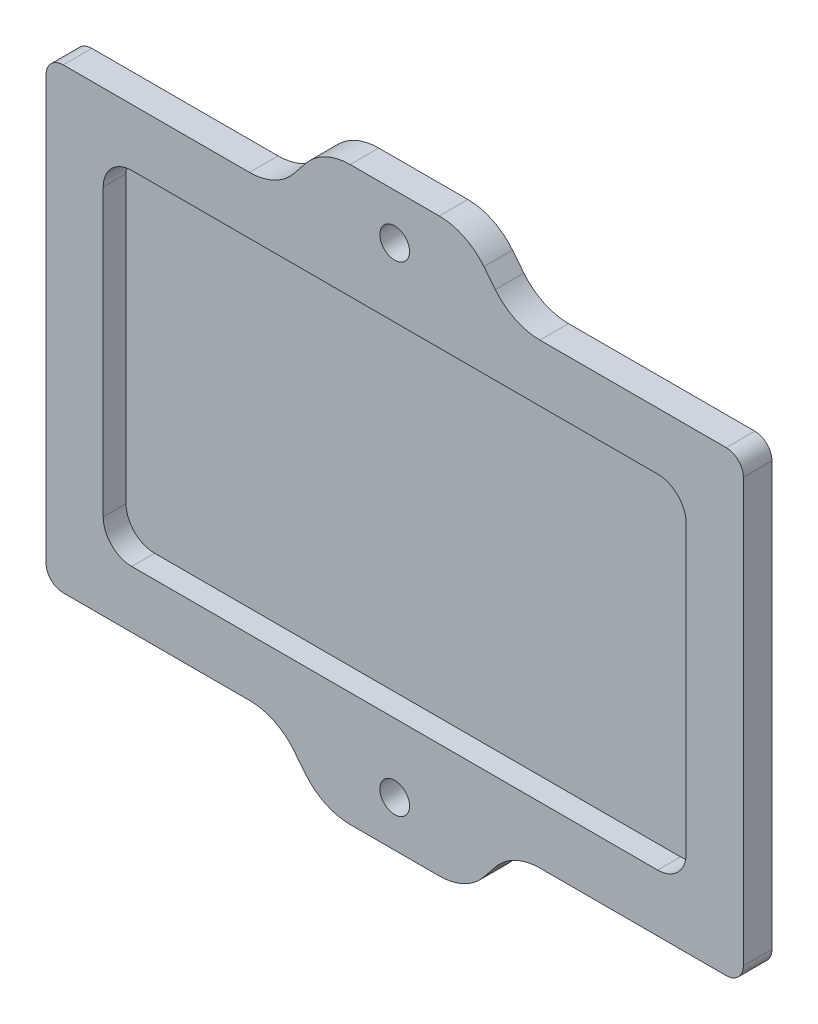
SolidWorks part; units mm, degrees
material "6063-O"
ref_plane "Front Plane" through (0, 0, 0) normal (0, 0, 1) x (1, 0, 0)
ref_plane "Top Plane" through (0, 0, 0) normal (0, 1, 0) x (1, 0, 0)
ref_plane "Right Plane" through (0, 0, 0) normal (1, 0, 0) x (0, 0, -1)
sketch "Sketch1" plane through (0, 0, 0) normal (0, 0, 1) x (1, 0, 0)
  line L1 (-42.6192, 65.8813) -> (73.3808, 65.8813)
  line L2 (-45.6192, 62.8813) -> (-45.6192, -41.1187)
  line L3 (-42.6192, -44.1187) -> (73.3808, -44.1187)
  line L4 (76.3808, 62.8813) -> (76.3808, -41.1187)
  arc A0 (-45.6192, -41.1187) -> (-42.6192, -44.1187) centre (-42.6192, -41.1187) ccw
  arc A1 (73.3808, -44.1187) -> (76.3808, -41.1187) centre (73.3808, -41.1187) ccw
  arc A2 (76.3808, 62.8813) -> (73.3808, 65.8813) centre (73.3808, 62.8813) ccw
  arc A3 (-45.6192, 62.8813) -> (-42.6192, 65.8813) centre (-42.6192, 62.8813) cw
  point P6 (-45.6192, -44.1187)
  point P11 (76.3808, 65.8813)
  point P14 (-45.6192, 65.8813)
  dimension "D3" = 3
  dimension "D1" = 122
  dimension "D2" = 110
extrude "Boss-Extrude1" add sketch "Sketch1" along normal blind 5
sketch "Sketch3" plane through (0, 0, 5) normal (0, 0, 1) x (1, 0, 0)
  line L0 (-45.6192, 62.8813) -> (-45.6192, -41.1187) construction
  line L2 (73.3808, 65.8813) -> (-42.6192, 65.8813) construction
  line L5 (-42.6192, -44.1187) -> (73.3808, -44.1187) construction
  line L6 (15.3808, 24.2476) -> (15.3808, -7.2931) construction
  line L8 (40.7873, 50.8813) -> (76.3808, 50.8813)
  line L9 (76.3808, -41.1187) -> (76.3808, 62.8813) construction
  line L10 (23.9808, 65.8813) -> (32.9787, 54.6343)
  line L11 (23.9808, 65.8813) -> (13.4808, 65.8813)
  line L13 (-10.0257, 50.8813) -> (-45.6192, 50.8813)
  line L14 (6.7808, 65.8813) -> (-2.217, 54.6343)
  line L15 (-57.8903, 10.8813) -> (91.1459, 10.8813) construction
  line L16 (40.7873, -29.1187) -> (76.3808, -29.1187)
  line L17 (23.9808, -44.1187) -> (32.9787, -32.8716)
  line L18 (6.7808, -44.1187) -> (-2.217, -32.8716)
  line L19 (-10.0257, -29.1187) -> (-45.6192, -29.1187)
  line L20 (-45.6192, 50.8813) -> (-45.6192, 81.1365)
  line L21 (-45.6192, 81.1365) -> (6.7808, 81.1365)
  line L22 (6.7808, 81.1365) -> (6.7808, 65.8813)
  line L23 (23.9808, 81.1365) -> (23.9808, 65.8813)
  line L24 (76.3808, 50.8813) -> (76.3808, 81.1365)
  line L25 (76.3808, 81.1365) -> (23.9808, 81.1365)
  line L26 (76.3808, -29.1187) -> (76.3808, -59.3739)
  line L27 (23.9808, -59.3739) -> (23.9808, -44.1187)
  line L28 (76.3808, -59.3739) -> (23.9808, -59.3739)
  line L29 (-45.6192, -29.1187) -> (-45.6192, -59.3739)
  line L30 (6.7808, -59.3739) -> (6.7808, -44.1187)
  line L31 (-45.6192, -59.3739) -> (6.7808, -59.3739)
  circle A0 centre (15.3808, 52.8813) radius 2.6
  circle A1 centre (15.3808, -31.1187) radius 2.6
  arc A2 (40.7873, 50.8813) -> (32.9787, 54.6343) centre (40.7873, 60.8813) cw
  arc A3 (-10.0257, 50.8813) -> (-2.217, 54.6343) centre (-10.0257, 60.8813) ccw
  arc A4 (40.7873, -29.1187) -> (32.9787, -32.8716) centre (40.7873, -39.1187) ccw
  arc A5 (-10.0257, -29.1187) -> (-2.217, -32.8716) centre (-10.0257, -39.1187) cw
  arc M1 (-45.6192, -41.1187) -> (-42.6192, -44.1187) centre (-42.6192, -41.1187) ccw
  line M2 (-42.6192, -44.1187) -> (73.3808, -44.1187)
  arc M3 (73.3808, -44.1187) -> (76.3808, -41.1187) centre (73.3808, -41.1187) ccw
  line M4 (76.3808, -41.1187) -> (76.3808, 62.8813)
  arc M5 (76.3808, 62.8813) -> (73.3808, 65.8813) centre (73.3808, 62.8813) ccw
  line M6 (73.3808, 65.8813) -> (-42.6192, 65.8813)
  arc M7 (-42.6192, 65.8813) -> (-45.6192, 62.8813) centre (-42.6192, 62.8813) ccw
  line M8 (-45.6192, 62.8813) -> (-45.6192, -41.1187)
  dimension "D2" = 0
  dimension "D4" = 13
  dimension "D5" = 10
  dimension "D1" = 52.4
  dimension "D6" = 55
  dimension "D7" = 40
extrude "Cut-Extrude1" cut sketch "Sketch3" against normal blind 10 contours L22 L21 L20 M7 M6 | L13 A3 L14 M6 M7 M8 | L24 L25 L23 M6 M5 | A2 L8 L10 M4 M5 M6 | L16 A4 L17 M2 M3 M4 | L28 L26 L27 M3 M2 | A5 L19 L18 M8 M1 M2 | L29 L31 L30 M2 M1 | A1
fillet "Fillet1" radius 10 4 edges at (6.7808, 65.8813, 2.5) (23.9808, 65.8813, 2.5) (6.7808, -44.1187, 2.5) (23.9808, -44.1187, 2.5)
fillet "Fillet2" radius 3 4 edges at (-45.6192, 50.8813, 2.5) (-45.6192, -29.1187, 2.5) (76.3808, 50.8813, 2.5) (76.3808, -29.1187, 2.5)
sketch "Sketch4" plane through (0, 0, 5) normal (0, 0, 1) x (1, 0, 0)
  line L0 (76.3808, -26.1187) -> (76.3808, 47.8813) construction
  circle A0 centre (15.3808, 52.8813) radius 2.6
  dimension "D1" = 61
  dimension "D2" = 13
  dimension "D3" = 5.2
extrude "Cut-Extrude2" cut sketch "Sketch4" against normal blind 10
sketch "Sketch5" plane through (0, 0, 5) normal (0, 0, 1) x (1, 0, 0)
  line L0 (-45.6192, 47.8813) -> (-45.6192, -26.1187) construction
  line L1 (-30.6192, 40.8813) -> (61.3808, 40.8813)
  line L2 (-35.6192, 35.8813) -> (-35.6192, -14.1187)
  line L3 (-30.6192, -19.1187) -> (61.3808, -19.1187)
  line L4 (66.3808, 35.8813) -> (66.3808, -14.1187)
  line L5 (-10.0257, 50.8813) -> (-42.6192, 50.8813) construction
  line L6 (-10.0257, -29.1187) -> (-42.6192, -29.1187) construction
  line L7 (76.3808, -26.1187) -> (76.3808, 47.8813) construction
  arc A0 (61.3808, 40.8813) -> (66.3808, 35.8813) centre (61.3808, 35.8813) cw
  arc A1 (61.3808, -19.1187) -> (66.3808, -14.1187) centre (61.3808, -14.1187) ccw
  arc A2 (-35.6192, -14.1187) -> (-30.6192, -19.1187) centre (-30.6192, -14.1187) ccw
  arc A3 (-35.6192, 35.8813) -> (-30.6192, 40.8813) centre (-30.6192, 35.8813) cw
  point P10 (66.3808, 10.8813)
  dimension "D5" = 5
  dimension "D1" = 10
  dimension "D2" = 10
  dimension "D3" = 10
  dimension "D4" = 10
extrude "Cut-Extrude3" cut sketch "Sketch5" against normal blind 4
sketch "Sketch6" plane through (0, 0, 5) normal (0, 0, 1) x (1, 0, 0)
  line L0 (23.1659, 60.8813) -> (7.5958, 60.8813)
  line L1 (30.992, 57.1065) -> (32.8197, 58.5603)
  line L2 (15.3808, 52.8813) -> (15.3808, 57.1577) construction
  line L3 (-0.2303, 57.1065) -> (-2.058, 58.5603)
  line L4 (-2.058, 58.5603) -> (6.6797, 70.4005)
  line L5 (6.6797, 70.4005) -> (28.4788, 70.4005)
  line L6 (28.4788, 70.4005) -> (32.8197, 58.5603)
  line L7 (15.3808, 60.8813) -> (15.3808, 72.5132) construction
  line L8 (-53.3834, 10.8813) -> (113.8126, 10.8813) construction
  line L9 (-10.0257, 50.8813) -> (-42.6192, 50.8813) construction
  line L10 (15.3808, -39.1187) -> (15.3808, -50.7505) construction
  line L11 (15.3808, -31.1187) -> (15.3808, -35.395) construction
  line L12 (28.4788, -48.6378) -> (32.8197, -36.7976)
  line L13 (6.6797, -48.6378) -> (28.4788, -48.6378)
  line L14 (-2.058, -36.7976) -> (6.6797, -48.6378)
  line L15 (-0.2303, -35.3438) -> (-2.058, -36.7976)
  line L16 (30.992, -35.3438) -> (32.8197, -36.7976)
  line L17 (23.1659, -39.1187) -> (7.5958, -39.1187)
  arc A0 (30.992, 57.1065) -> (23.1659, 60.8813) centre (23.1659, 50.8813) ccw
  arc A1 (7.5958, 60.8813) -> (-0.2303, 57.1065) centre (7.5958, 50.8813) ccw
  arc A2 (7.5958, -39.1187) -> (-0.2303, -35.3438) centre (7.5958, -29.1187) cw
  arc A3 (30.992, -35.3438) -> (23.1659, -39.1187) centre (23.1659, -29.1187) cw
  dimension "D1" = 38.5
  dimension "D2" = 40
extrude "Cut-Extrude4" cut sketch "Sketch6" against normal blind 10
